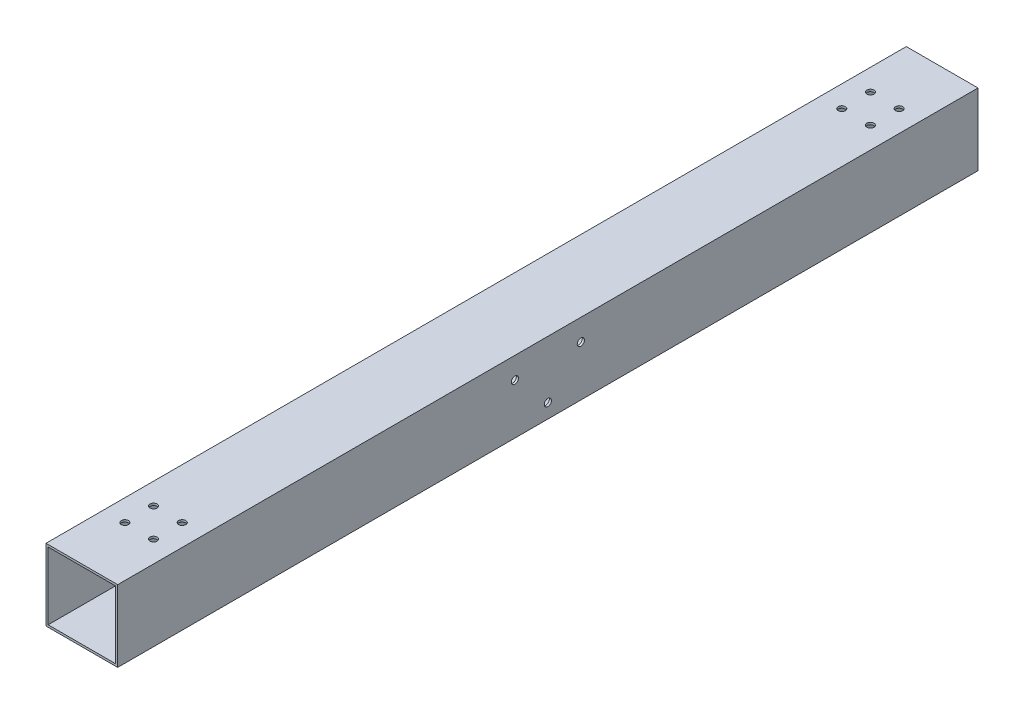
SolidWorks part; units mm, degrees
material "6061 Alloy"
ref_plane "Front Plane" through (0, 0, 0) normal (0, 0, 1) x (1, 0, 0)
ref_plane "Top Plane" through (0, 0, 0) normal (0, 1, 0) x (1, 0, 0)
ref_plane "Right Plane" through (0, 0, 0) normal (1, 0, 0) x (0, 0, -1)
sketch "Sketch1" plane through (0, 0, 0) normal (0, 0, 1) x (1, 0, 0)
  line L1 (-23.5, 23.5) -> (23.5, 23.5)
  line L2 (-23.5, 23.5) -> (-23.5, -23.5)
  line L3 (-23.5, -23.5) -> (23.5, -23.5)
  line L4 (23.5, 23.5) -> (23.5, -23.5)
  line L5 (-23.5, 23.5) -> (23.5, -23.5) construction
  line L6 (-23.5, -23.5) -> (23.5, 23.5) construction
  line L7 (-25, 25) -> (25, 25)
  line L8 (-25, 25) -> (-25, -25)
  line L9 (-25, -25) -> (25, -25)
  line L10 (25, 25) -> (25, -25)
  line L11 (-25, 25) -> (25, -25) construction
  line L12 (-25, -25) -> (25, 25) construction
  point P0 (0, 0)
  point P6 (0, 0)
  dimension "D1" = 50
  dimension "D2" = 47
  dimension "D3" = 50
  dimension "D4" = 47
extrude "Boss-Extrude1" add sketch "Sketch1" along normal blind 600
sketch "Sketch2" plane through (25, 0, 0) normal (1, 0, 0) x (0, 0, -1)
  line L0 (-600, -25) -> (0, -25) construction
  line L1 (-300, -25) -> (-300, 25) construction
  line L2 (-600, 25) -> (0, 25) construction
  line L3 (0, -25) -> (0, 25) construction
  circle A0 centre (-300, -15) radius 2.5
  circle A1 centre (-277, 10) radius 2.5
  circle A2 centre (-323, 10) radius 2.5
  point P0 (-300, -25)
  dimension "D4" = 5
  dimension "D1" = 10
  dimension "D2" = 25
  dimension "D3" = 23
  dimension "D5" = 300
extrude "Cut-Extrude1" cut sketch "Sketch2" against normal blind 59
ref_plane "Plane1" through (0, 0, 450) normal (0, 0, 1) x (1, 0, 0)
sketch "Sketch3" plane through (0, 25, 0) normal (0, 1, 0) x (1, 0, 0)
  line L0 (0, 0) -> (0, -600) construction
  line L1 (25, -600) -> (-25, -600) construction
  line L2 (-25, -300) -> (25, -300) construction
  line L3 (-25, -600) -> (-25, 0) construction
  line L4 (25, -600) -> (25, 0) construction
  line L5 (-37.0377, -50) -> (37.9441, -50) construction
  circle A0 centre (-10, -40) radius 2.5
  circle A1 centre (10, -40) radius 2.5
  circle A2 centre (-10, -60) radius 2.5
  circle A3 centre (10, -60) radius 2.5
  circle A4 centre (10, -540) radius 2.5
  circle A5 centre (-10, -540) radius 2.5
  circle A6 centre (10, -560) radius 2.5
  circle A7 centre (-10, -560) radius 2.5
  dimension "D1" = 5
  dimension "D2" = 10
  dimension "D3" = 5
  dimension "D4" = 10
  dimension "D5" = 10
  dimension "D6" = 10
  dimension "D7" = 250
extrude "Cut-Extrude2" cut sketch "Sketch3" against normal through all
